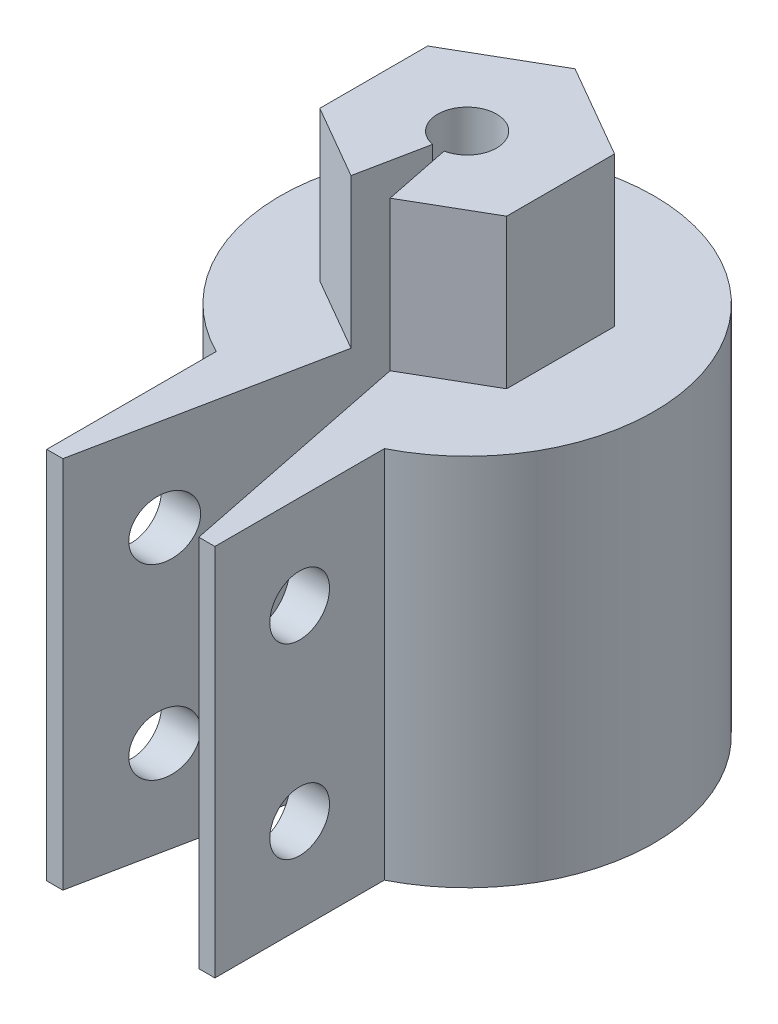
SolidWorks part; units mm, degrees
ref_plane "正面" through (0, 0, 0) normal (0, 0, 1) x (1, 0, 0)
ref_plane "平面" through (0, 0, 0) normal (0, 1, 0) x (1, 0, 0)
ref_plane "右側面" through (0, 0, 0) normal (1, 0, 0) x (0, 0, -1)
sketch "ｽｹｯﾁ1" plane through (0, 0, 0) normal (0, 1, 0) x (1, 0, 0)
  line L6 (-4.5, -8.9303) -> (-4.5, -18)
  line L7 (-4.5, -18) -> (4.5, -18)
  line L8 (4.5, -8.9303) -> (4.5, -18)
  arc A0 (4.5, -8.9303) -> (-4.5, -8.9303) centre (0, 0) ccw
  point P1 (0, -18)
  dimension "D1" = 20
  dimension "D3" = 9
  dimension "D4" = 18
extrude "ﾎﾞｽ - 押し出し1" add sketch "ｽｹｯﾁ1" along normal blind 20
sketch "ｽｹｯﾁ2" plane through (0, 20, 0) normal (0, 1, 0) x (1, 0, 0)
  line L5 (0, 5.7735) -> (-5, 2.8868)
  line L6 (-5, 2.8868) -> (-5, -2.8868)
  line L7 (-5, -2.8868) -> (0, -5.7735)
  line L8 (0, -5.7735) -> (5, -2.8868)
  line L9 (5, -2.8868) -> (5, 2.8868)
  line L10 (5, 2.8868) -> (0, 5.7735)
  circle A0 centre (0, 0) radius 5 construction
  dimension "D1" = 10
extrude "ﾎﾞｽ - 押し出し2" add sketch "ｽｹｯﾁ2" along normal blind 8
sketch "ｽｹｯﾁ3" plane through (0, 28, 0) normal (0, 1, 0) x (1, 0, 0)
  line L5 (-4.5, -18) -> (4.5, -18) construction
  line L6 (-3.6388, -18) -> (-0.3121, -1.5438)
  line L7 (0.3121, -1.5438) -> (3.6388, -18)
  arc A1 (0.3121, -1.5438) -> (-0.3121, -1.5438) centre (0, 0) ccw
  arc A2 (-3.6388, -18) -> (3.6388, -18) centre (0, 0) ccw
  point P1 (0, -18.3641)
  dimension "D1" = 3.15
  dimension "D2" = 19.1637
extrude "ｶｯﾄ - 押し出し1" cut sketch "ｽｹｯﾁ3" against normal through all
sketch "ｽｹｯﾁ4" plane through (-4.5, 0, 0) normal (-1, 0, 0) x (0, 0, 1)
  line L0 (8.9303, 20) -> (18, 20) construction
  line L1 (8.9303, 0) -> (18, 0) construction
  circle A0 centre (13.4651, 15) radius 1.6
  circle A1 centre (13.4651, 5) radius 1.6
  point P8 (13.4651, 20)
  dimension "D3" = 3.2
  dimension "D1" = 5
  dimension "D2" = 5
extrude "ｶｯﾄ - 押し出し2" cut sketch "ｽｹｯﾁ4" against normal through all
equation "\"D2@ｽｹｯﾁ3\"=2*PI*(3.05)"
